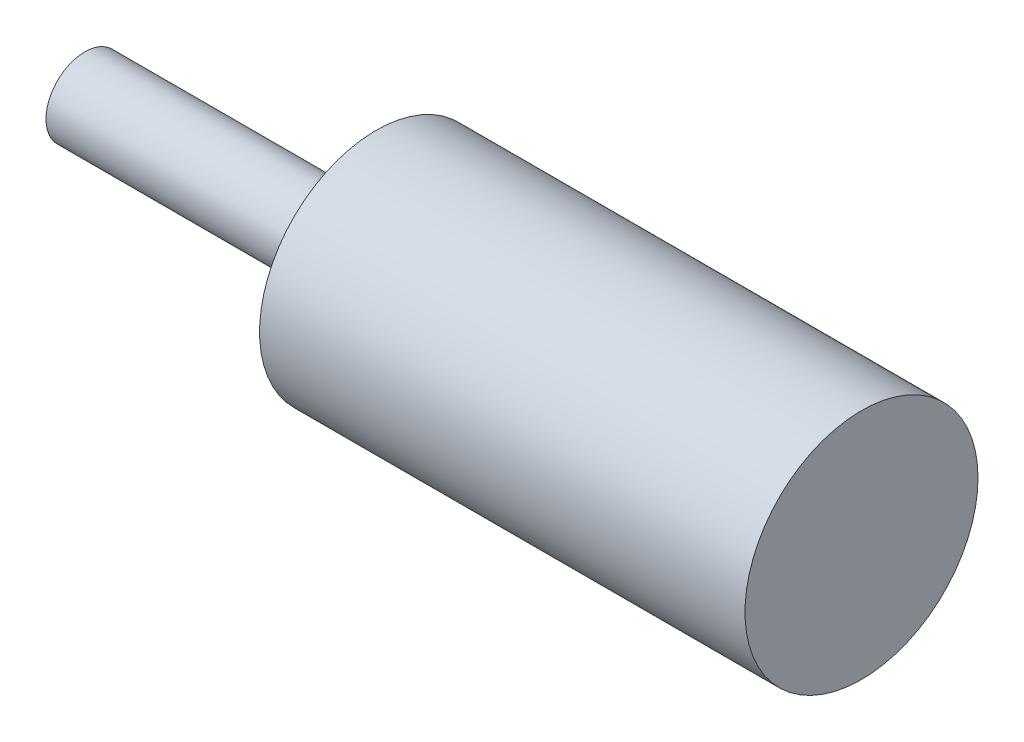
SolidWorks part; units mm, degrees
ref_plane "Front Plane" through (0, 0, 0) normal (0, 0, 1) x (1, 0, 0)
ref_plane "Top Plane" through (0, 0, 0) normal (0, 1, 0) x (1, 0, 0)
ref_plane "Right Plane" through (0, 0, 0) normal (1, 0, 0) x (0, 0, -1)
sketch "Sketch1" plane through (0, 0, 0) normal (1, 0, 0) x (0, 0, -1)
  circle A0 centre (0, 0) radius 6
  dimension "D1" = 12
extrude "Boss-Extrude1" add sketch "Sketch1" along normal blind 25
sketch "Sketch2" plane through (0, 0, 0) normal (-1, 0, 0) x (0, 0, 1)
  circle A0 centre (0, 0) radius 2
  dimension "D1" = 4
extrude "Boss-Extrude2" add sketch "Sketch2" along normal blind 15
fillet "Fillet1" radius 1 1 edges at (0, 0, -2)
